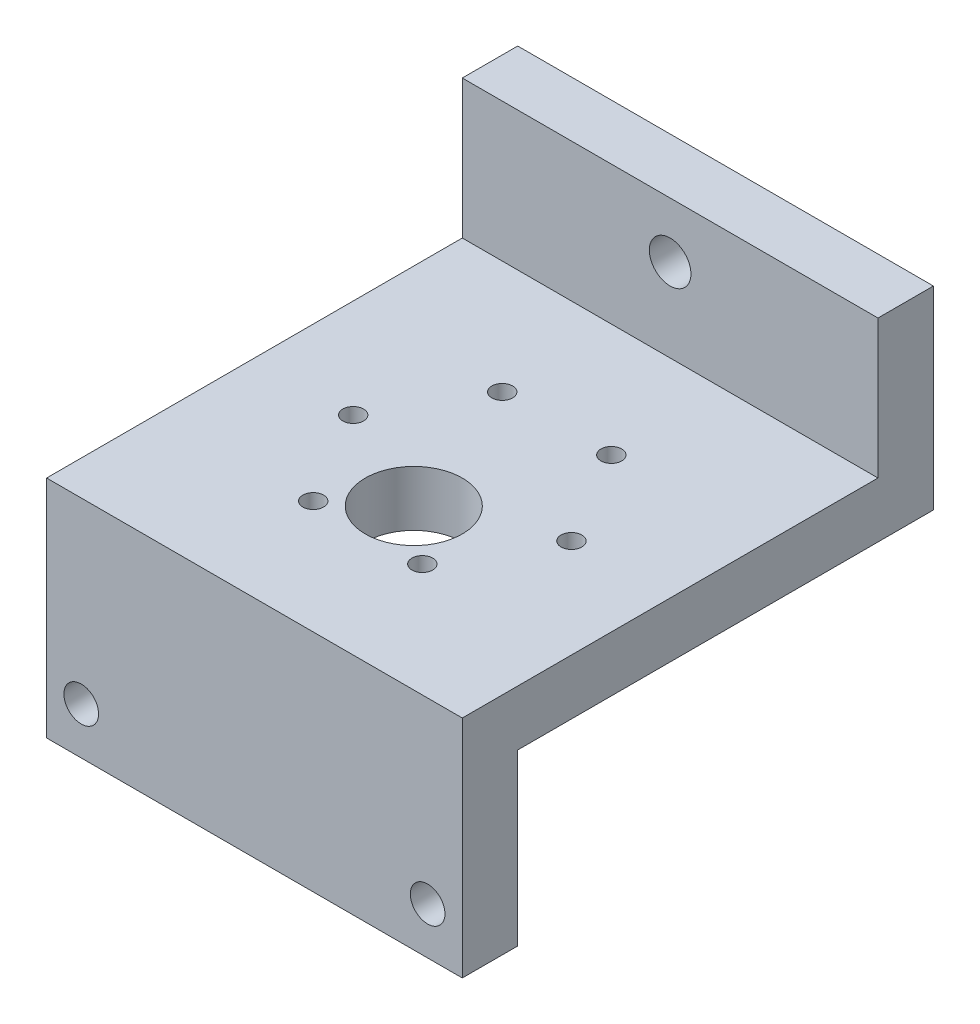
SolidWorks part; units mm, degrees
ref_plane "Front Plane" through (0, 0, 0) normal (0, 0, 1) x (1, 0, 0)
ref_plane "Top Plane" through (0, 0, 0) normal (0, 1, 0) x (1, 0, 0)
ref_plane "Right Plane" through (0, 0, 0) normal (1, 0, 0) x (0, 0, -1)
sketch "Sketch1" plane through (0, 0, 0) normal (1, 0, 0) x (0, 0, -1)
  line L1 (0, 20) -> (0, 0)
  line L2 (0, 0) -> (-52, 0)
  line L3 (-52, 0) -> (-52, -8)
  line L4 (-52, -8) -> (8, -8)
  line L5 (8, -8) -> (8, 20)
  line L6 (8, 20) -> (0, 20)
  dimension "D1" = 52
  dimension "D2" = 8
  dimension "D3" = 8
  dimension "D4" = 20
extrude "Boss-Extrude1" add sketch "Sketch1" along normal mid plane 60
sketch "Sketch2" plane through (0, 0, 0) normal (0, 1, 0) x (1, 0, 0)
  circle A0 centre (0, -37) radius 7
  circle A1 centre (15.75, -30) radius 1.5
  circle A2 centre (7.875, -43.6399) radius 1.5
  circle A3 centre (-7.875, -43.6399) radius 1.5
  circle A4 centre (-15.75, -30) radius 1.5
  circle A5 centre (-7.875, -16.3601) radius 1.5
  circle A6 centre (7.875, -16.3601) radius 1.5
  point P5 (0, -30)
  point P19 (0, -30)
  dimension "D2" = 14
  dimension "D5" = 3
  dimension "D1" = 37
  dimension "D3" = 7
  dimension "D4" = 15.75
  dimension "D6" = 6
extrude "Cut-Extrude1" cut sketch "Sketch2" against normal blind 55
sketch "Sketch3" plane through (0, 0, 0) normal (0, 0, 1) x (1, 0, 0)
  circle A0 centre (0, 12) radius 3
  dimension "D1" = 6
  dimension "D2" = 12
extrude "Cut-Extrude2" cut sketch "Sketch3" against normal blind 55
sketch "Sketch4" plane through (30, 0, 0) normal (1, 0, 0) x (0, 0, -1)
  line L1 (-52, 0) -> (-60, 0)
  line L2 (-52, 0) -> (-52, -40)
  line L3 (-52, -40) -> (-60, -40)
  line L4 (-60, 0) -> (-60, -40)
  dimension "D1" = 8
  dimension "D2" = 40
extrude "Boss-Extrude2" add sketch "Sketch4" against normal up to vertex (60 mm away)
sketch "Sketch5" plane through (0, 0, 60) normal (0, 0, 1) x (1, 0, 0)
  circle A0 centre (25, -25.75) radius 2.5 construction
  circle A1 centre (-25, -25.75) radius 2.5 construction
  circle A2 centre (25, -25.75) radius 2.5
  circle A3 centre (-25, -25.75) radius 2.5
extrude "Cut-Extrude3" cut sketch "Sketch5" against normal blind 10
sketch "Sketch6" plane through (-30, 0, 0) normal (-1, 0, 0) x (0, 0, 1)
  line L0 (66, -32.5) -> (60, -32.5) construction
  line L1 (66, -32.5) -> (60, -32.5)
  line L2 (52, -40) -> (52, -8) construction
  line L3 (60, -40) -> (52, -40)
  line L4 (60, -40) -> (60, -32.5)
  line L5 (60, -32.5) -> (52, -32.5)
  line L6 (52, -40) -> (52, -32.5)
  line M4 (52, -8) -> (52, -40)
  line M5 (52, -40) -> (60, -40)
  line M6 (60, -40) -> (60, 0)
extrude "Cut-Extrude4" cut sketch "Sketch6" against normal through all contours L5 M6 M4 M5
